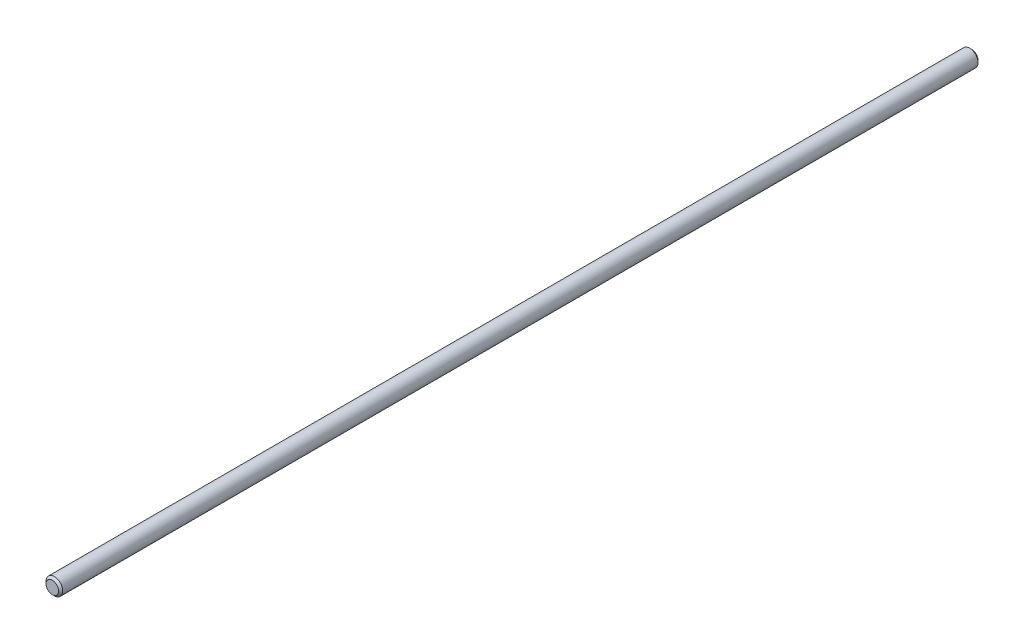
SolidWorks part; units mm, degrees
ref_plane "Front (XY)" through (0, 0, 0) normal (0, 0, 1) x (1, 0, 0)
ref_plane "Top (XZ)" through (0, 0, 0) normal (0, 1, 0) x (1, 0, 0)
ref_plane "Right (YZ)" through (0, 0, 0) normal (1, 0, 0) x (0, 0, -1)
sketch "Sketch1" plane through (0, 0, 0) normal (0, 0, 1) x (1, 0, 0)
  circle A0 centre (0, 0) radius 4
  dimension "D1" = 8
extrude "Boss-Extrude1" add sketch "Sketch1" along normal blind 440
chamfer "Chamfer1" distance 1 angle 45 2 edges at (4, 0, 440) (4, 0, 0)
